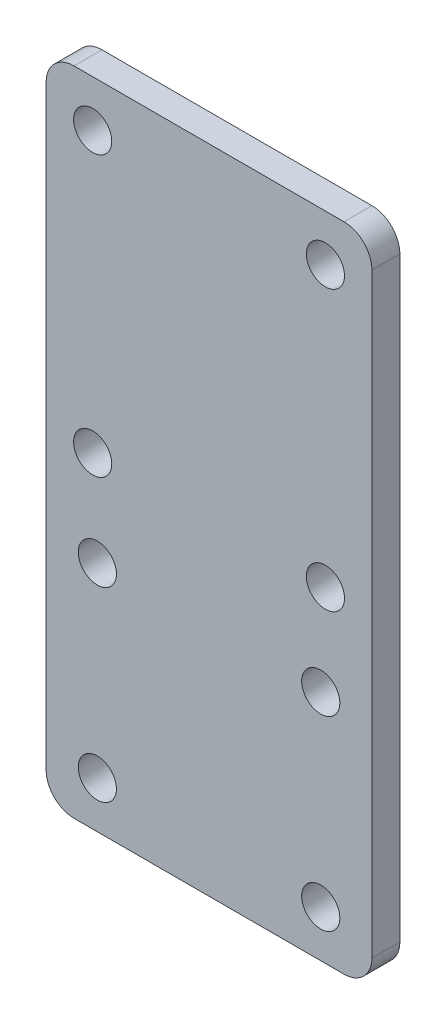
SolidWorks part; units mm, degrees
material "E-玻璃纤维"
ref_plane "前视基准面" through (0, 0, 0) normal (0, 0, 1) x (1, 0, 0)
ref_plane "上视基准面" through (0, 0, 0) normal (0, 1, 0) x (1, 0, 0)
ref_plane "右视基准面" through (0, 0, 0) normal (1, 0, 0) x (0, 0, -1)
other "Configuration Table"
sketch "草图1" plane through (0, 0, 0) normal (0, 0, 1) x (1, 0, 0)
  line L0 (0, 20.1388) -> (0, -18.2641) construction
  line L1 (-17.5, 35) -> (17.5, 35)
  line L2 (-17.5, 35) -> (-17.5, -35)
  line L3 (-17.5, -35) -> (17.5, -35)
  line L4 (17.5, 35) -> (17.5, -35)
  line L5 (-17.5, 35) -> (17.5, -35) construction
  line L6 (-17.5, -35) -> (17.5, 35) construction
  line L8 (-12.5, 30) -> (12.5, 30) construction
  line L9 (-12.5, 30) -> (-12.5, 0) construction
  line L10 (-12.5, 0) -> (12.5, 0) construction
  line L11 (12.5, 30) -> (12.5, 0) construction
  line L12 (-12.5, 30) -> (12.5, 0) construction
  line L13 (-12.5, 0) -> (12.5, 30) construction
  line L14 (-12, -10) -> (12, -10) construction
  line L15 (-12, -10) -> (-12, -30) construction
  line L16 (-12, -30) -> (12, -30) construction
  line L17 (12, -10) -> (12, -30) construction
  line L18 (-12, -10) -> (12, -30) construction
  line L19 (-12, -30) -> (12, -10) construction
  circle A0 centre (-12.5, 30) radius 2.05
  circle A1 centre (-12.5, 0) radius 2.05
  circle A2 centre (12.5, 0) radius 2.05
  circle A3 centre (12.5, 30) radius 2.05
  circle A4 centre (-12, -10) radius 2.05
  circle A5 centre (-12, -30) radius 2.05
  circle A6 centre (12, -30) radius 2.05
  circle A7 centre (12, -10) radius 2.05
  point P0 (0, 0)
  point P8 (0, 15)
  point P17 (0, -20)
  dimension "D6" = 4.1
  dimension "D9" = 24
  dimension "D1" = 70
  dimension "D2" = 35
  dimension "D3" = 30
  dimension "D4" = 5
  dimension "D5" = 25
  dimension "D7" = 20
  dimension "D8" = 5
extrude "凸台-拉伸1" add sketch "草图1" along normal blind 3
fillet "圆角1" radius 3 4 edges at (17.5, -35, 1.5) (-17.5, -35, 1.5) (17.5, 35, 1.5) (-17.5, 35, 1.5)
